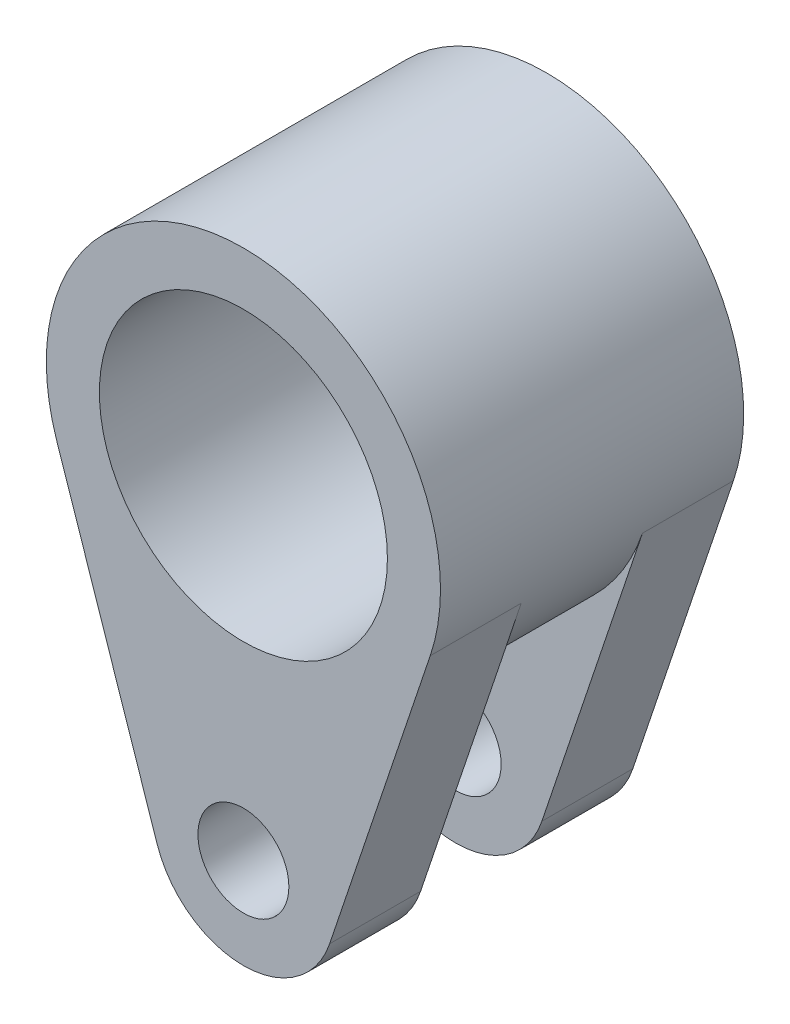
SolidWorks part; units mm, degrees
ref_plane "Front Plane" through (0, 0, 0) normal (1, 0, 0) x (0, 1, 0)
ref_plane "Top Plane" through (0, 0, 0) normal (0, 0, 1) x (0, 1, 0)
ref_plane "Right Plane" through (0, 0, 0) normal (0, 1, 0) x (-1, 0, 0)
sketch "Sketch1" plane through (0, 0, 0) normal (0, 0, 1) x (0, 1, 0)
  circle A0 centre (0, 0) radius 13
  dimension "D1" = 26
extrude "Boss-Extrude1" add sketch "Sketch1" along normal mid plane 20
sketch "Sketch2" plane through (0, 0, 10) normal (0, 0, 1) x (1, 0, 0)
  line L0 (-12.3244, -4.1364) -> (-5.6882, -23.9091)
  line L1 (0, 0) -> (0, -22) construction
  line L2 (12.3244, -4.1364) -> (5.6882, -23.9091)
  arc A0 (12.3244, -4.1364) -> (-12.3244, -4.1364) centre (0, 0) ccw
  circle A1 centre (0, -22) radius 3
  arc A2 (-5.6882, -23.9091) -> (5.6882, -23.9091) centre (0, -22) ccw
  dimension "D1" = 26
  dimension "D2" = 6
  dimension "D4" = 12
  dimension "D3" = 22
extrude "Boss-Extrude2" add sketch "Sketch2" against normal blind 6
mirror "Mirror1" about plane through (0, 0, 0) normal (0, 0, 1) of "Boss-Extrude2"
sketch "Sketch3" plane through (0, 0, 10) normal (0, 0, 1) x (1, 0, 0)
  circle A0 centre (0, 0) radius 9.5
  dimension "D1" = 19
extrude "Cut-Extrude1" cut sketch "Sketch3" against normal through all both and the other way through all
